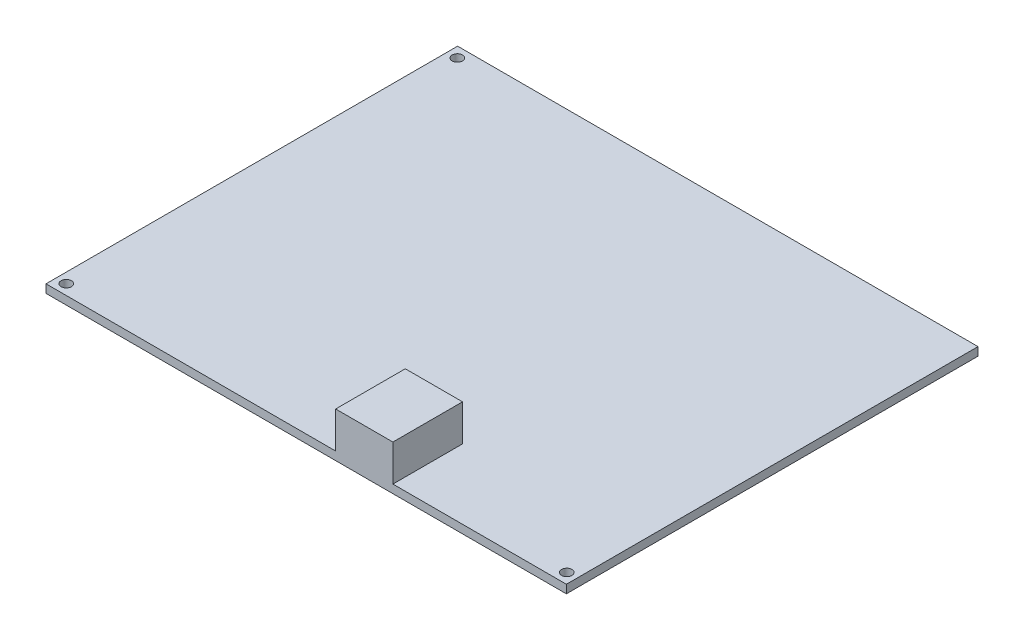
SolidWorks part; units mm, degrees
ref_plane "前视基准面" through (0, 0, 0) normal (0, 0, 1) x (1, 0, 0)
ref_plane "上视基准面" through (0, 0, 0) normal (0, 1, 0) x (1, 0, 0)
ref_plane "右视基准面" through (0, 0, 0) normal (1, 0, 0) x (0, 0, -1)
other "Configuration Table"
sketch "草图1" plane through (0, 0, 0) normal (0, 1, 0) x (1, 0, 0)
  line L1 (0, 0) -> (100, 0)
  line L2 (0, 0) -> (0, 79.1)
  line L3 (0, 79.1) -> (100, 79.1)
  line L4 (100, 0) -> (100, 79.1)
  circle A0 centre (1.942, 77.109) radius 1
  circle A1 centre (1.93, 1.968) radius 1
  circle A2 centre (98.066, 2.005) radius 1
  dimension "D3" = 2
  dimension "D4" = 1.942
  dimension "D5" = 77.109
  dimension "D7" = 1.968
  dimension "D8" = 2.005
  dimension "D9" = 98.066
  dimension "D1" = 79.1
  dimension "D2" = 100
  dimension "D6" = 1.93
extrude "凸台-拉伸1" add sketch "草图1" along normal blind 1.6
sketch "草图2" plane through (0, 1.6, 0) normal (0, 1, 0) x (1, 0, 0)
  line L0 (0, 0) -> (100, 0) construction
  line L1 (55.663, 0) -> (66.663, 0)
  line L2 (55.663, 0) -> (55.663, 13.382)
  line L3 (55.663, 13.382) -> (66.663, 13.382)
  line L4 (66.663, 0) -> (66.663, 13.382)
  line L5 (0, 79.1) -> (0, 0) construction
  dimension "D1" = 11
  dimension "D2" = 55.663
  dimension "D3" = 13.382
extrude "凸台-拉伸2" add sketch "草图2" along normal blind 7
